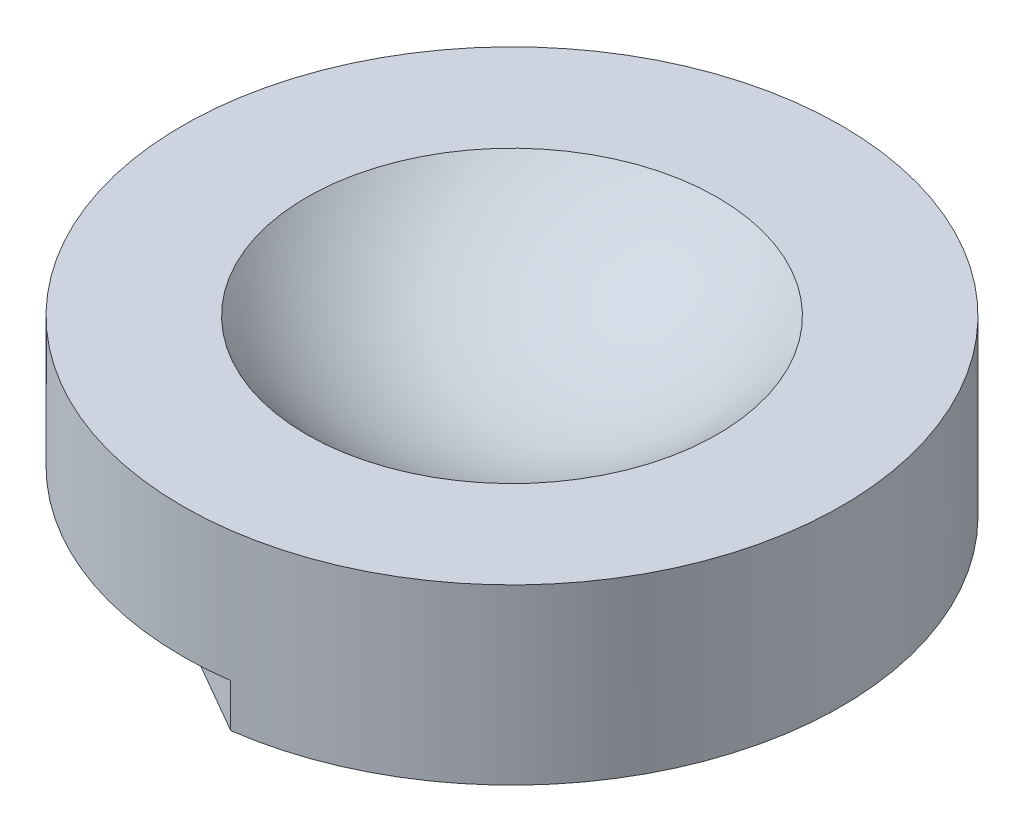
SolidWorks part; units mm, degrees
other "Fixed Steel Cup Liner 2"
other "Fixed Steel Cup Liner 2 Left"
ref_plane "Front Plane" through (0, 0, 0) normal (0, 0, 1) x (1, 0, 0)
ref_plane "Top Plane" through (0, 0, 0) normal (0, 1, 0) x (1, 0, 0)
ref_plane "Right Plane" through (0, 0, 0) normal (1, 0, 0) x (0, 0, -1)
sketch3d "Keyed Back Sketch datum points"
  point P0 (-56.2917, -69, 0)
  point P1 (-46.2917, -69, 0)
  point P2 (-56.2917, -69, 10)
ref_plane "Keyed Back Sketch plane" through (0, -69, 0) normal (0, -1, 0) x (-1, 0, 0)
sketch "Keyed Back Sketch" plane through (0, -69, 0) normal (0, -1, 0) x (-1, 0, 0)
  line L0 (70.7718, -29.745) -> (74.8116, -27.4126)
  arc A0 (74.8116, -27.4126) -> (70.7718, -29.745) centre (71.2917, -25.9808) ccw
extrude "Keyed Back" add sketch "Keyed Back Sketch" along normal blind 0.5 separate body
sketch3d "Cup Blank Sketch datum points"
  point P0 (-56.2917, -69.5, 0)
  point P1 (-46.2917, -69.5, 0)
  point P2 (-56.2917, -69.5, 10)
ref_plane "Cup Blank Sketch plane" through (0, -69.5, 0) normal (0, -1, 0) x (-1, 0, 0)
sketch "Cup Blank Sketch" plane through (0, -69.5, 0) normal (0, -1, 0) x (-1, 0, 0)
  circle A0 centre (71.2917, -25.9808) radius 3.8
extrude "Cup Blank" add sketch "Cup Blank Sketch" along normal blind 1.5
sketch3d "Spherical Bearing Seat axis line"
  line L0 (-71.2917, -73, 15.9808) -> (-71.2917, -73, 35.9808) construction
ref_axis "Spherical Bearing Seat axis" through (-71.2917, -73, 15.9808) along (0, 0, 1)
sketch3d "Spherical Bearing Seat profile datum points"
  point P0 (-71.2917, -73, 25.9808)
  point P1 (-61.2917, -73, 25.9808)
  point P2 (-71.2917, -73, 35.9808)
ref_plane "Spherical Bearing Seat profile plane" through (0, -73, 0) normal (0, -1, 0) x (-1, 0, 0)
sketch "Spherical Bearing Seat profile" plane through (0, -73, 0) normal (0, -1, 0) x (-1, 0, 0)
  line L0 (71.2917, -29.0808) -> (71.2917, -22.8808)
  arc A0 (71.2917, -22.8808) -> (71.2917, -29.0808) centre (71.2917, -25.9808) ccw
revolve "Spherical Bearing Seat" cut sketch "Spherical Bearing Seat profile" angle 360 about axis through (-71.2917, -73, 15.9808) along (0, 0, 1)
sketch3d "Mirror1 profile datum points"
  point P0 (0, 0, 0)
  point P1 (10, 0, 0)
  point P2 (0, 0, 10)
ref_plane "Mirror1 profile plane" through (0, 0, 0) normal (0, -1, 0) x (-1, 0, 0)
mirror "Mirror1" about plane through (0, 0, 0) normal (0, -1, 0) of bodies 103
delete or keep bodies "Remove1" type delete bodies bodies 103
